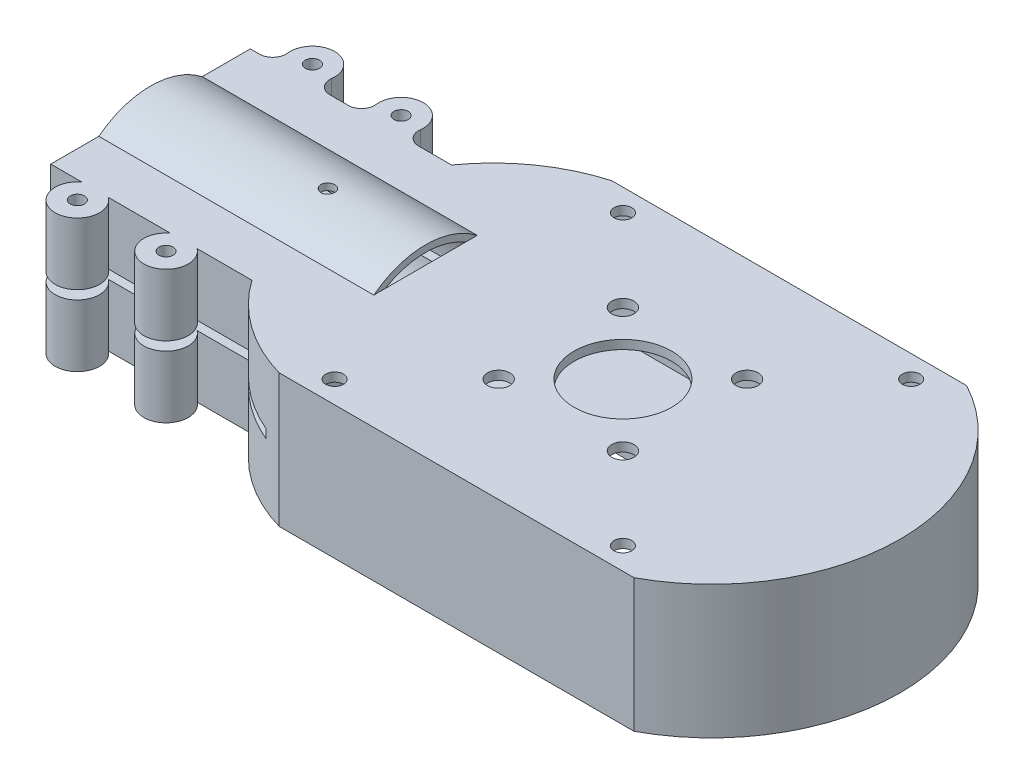
SolidWorks part; units mm, degrees
ref_plane "前视基准面" through (0, 0, 0) normal (0, 0, 1) x (1, 0, 0)
ref_plane "上视基准面" through (0, 0, 0) normal (0, 1, 0) x (1, 0, 0)
ref_plane "右视基准面" through (0, 0, 0) normal (1, 0, 0) x (0, 0, -1)
sketch "草图1" plane through (0, 0, 0) normal (0, 1, 0) x (1, 0, 0)
  line L1 (-40, -37.5) -> (40, -37.5)
  line L2 (-40, -37.5) -> (-40, 37.5)
  line L3 (-40, 37.5) -> (40, 37.5)
  line L4 (40, -37.5) -> (40, 37.5)
  line L5 (-40, -37.5) -> (40, 37.5) construction
  line L6 (-40, 37.5) -> (40, -37.5) construction
  arc A1 (-40, 37.5) -> (-40, -37.5) centre (-29.2879, 0) ccw
  arc A2 (40, -37.5) -> (40, 37.5) centre (20, 0) ccw
  point P0 (0, 0)
  dimension "D3" = 42.5
  dimension "D4" = 78
  dimension "D1" = 75
  dimension "D2" = 80
extrude "凸台-拉伸1" add sketch "草图1" along normal mid plane 30 contours L2 A1 | L1 L4 L3 L2 | L4 A2
ref_plane "基准面1" through (62.5, 0, 0) normal (1, 0, 0) x (0, 0, -1)
ref_plane "基准面2" through (-106.5, 0, 0) normal (1, 0, 0) x (0, 0, -1)
sketch "草图2" plane through (-106.5, 0, 0) normal (1, 0, 0) x (0, 0, -1)
  line L0 (37.5, 15) -> (-37.5, 15) construction
  line L1 (-22.5, -15) -> (22.5, -15)
  line L2 (-22.5, -15) -> (-22.5, 15)
  line L3 (-22.5, 15) -> (22.5, 15)
  line L4 (22.5, -15) -> (22.5, 15)
  line L5 (-22.5, -15) -> (22.5, 15) construction
  line L6 (-22.5, 15) -> (22.5, -15) construction
  point P0 (0, 0)
  dimension "D1" = 45
extrude "凸台-拉伸2" add sketch "草图2" along normal up to surface (45.357 mm away)
sketch "草图3" plane through (-106.5, 0, 0) normal (-1, 0, 0) x (0, 0, 1)
  circle A0 centre (0, 0) radius 19
  dimension "D1" = 38
extrude "凸台-拉伸3" add sketch "草图3" against normal blind 62
sketch "草图4" plane through (-106.5, 0, 0) normal (-1, 0, 0) x (0, 0, 1)
  circle A0 centre (0, 0) radius 17.5
  dimension "D1" = 35
extrude "切除-拉伸1" cut sketch "草图4" against normal blind 62
sketch "草图5" plane through (-106.5, 0, 0) normal (-1, 0, 0) x (0, 0, 1)
  line L1 (-39.0777, -1) -> (39.0777, -1)
  line L2 (-39.0777, -1) -> (-39.0777, 1)
  line L3 (-39.0777, 1) -> (39.0777, 1)
  line L4 (39.0777, -1) -> (39.0777, 1)
  line L5 (-39.0777, -1) -> (39.0777, 1) construction
  line L6 (-39.0777, 1) -> (39.0777, -1) construction
  point P0 (0, 0)
  dimension "D1" = 2
sketch "草图6" plane through (0, 15, 0) normal (0, 1, 0) x (1, 0, 0)
  line L0 (-61.143, 22.5) -> (-106.5, 22.5) construction
  line L1 (-106.5, 22.5) -> (-106.5, 11.6619) construction
  circle A0 centre (-96.5, 26.5) radius 5
  circle A1 centre (-76.5, 26.5) radius 5
  dimension "D1" = 4
  dimension "D2" = 10
  dimension "D3" = 20
  dimension "D4" = 10
  dimension "D5" = 10
extrude "凸台-拉伸4" add sketch "草图6" against normal up to surface (30 mm away) up to face at (-50.4537, -15, 0)
fillet "圆角1" radius 3 4 edges at (-93.5, 0, -22.5) (-99.5, 0, -22.5) (-73.5, 0, -22.5) (-79.5, 0, -22.5)
mirror "镜向3" about plane through (0, 0, 0) normal (0, 0, 1) of "凸台-拉伸4"
sketch "草图7" plane through (0, 15, 0) normal (0, 1, 0) x (1, 0, 0)
  circle A0 centre (-96.5, 26.5) radius 1.6
  circle A1 centre (-76.5, 26.5) radius 1.6
  circle A2 centre (-76.5, -26.5) radius 1.6
  circle A3 centre (-96.5, -26.5) radius 1.6
  dimension "D1" = 3.2
extrude "切除-拉伸3" cut sketch "草图7" against normal blind 62
extrude "切除-拉伸4" cut sketch "草图5" against normal blind 62 contours L1 L4 L3 L2
sketch "草图8" plane through (0, -15, 0) normal (0, -1, 0) x (1, 0, 0)
  circle A0 centre (0, 0) radius 11
  dimension "D1" = 22
extrude "切除-拉伸5" cut sketch "草图8" against normal blind 62
sketch "草图9" plane through (0, -15, 0) normal (0, -1, 0) x (1, 0, 0)
  line L1 (-14, -14) -> (14, -14) construction
  line L2 (-14, -14) -> (-14, 14) construction
  line L3 (-14, 14) -> (14, 14) construction
  line L4 (14, -14) -> (14, 14) construction
  line L5 (-14, -14) -> (14, 14) construction
  line L6 (-14, 14) -> (14, -14) construction
  circle A0 centre (14, 14) radius 2.5
  circle A1 centre (14, -14) radius 2.5
  circle A2 centre (-14, -14) radius 2.5
  circle A3 centre (-14, 14) radius 2.5
  point P0 (0, 0)
  dimension "D3" = 5
  dimension "D1" = 28
  dimension "D2" = 28
extrude "切除-拉伸6" cut sketch "草图9" against normal through all
sketch "草图10" plane through (0, 15, 0) normal (0, 1, 0) x (1, 0, 0)
  line L1 (-32.5, -32.5) -> (32.5, -32.5) construction
  line L2 (-32.5, -32.5) -> (-32.5, 32.5) construction
  line L3 (-32.5, 32.5) -> (32.5, 32.5) construction
  line L4 (32.5, -32.5) -> (32.5, 32.5) construction
  line L5 (-32.5, -32.5) -> (32.5, 32.5) construction
  line L6 (-32.5, 32.5) -> (32.5, -32.5) construction
  circle A0 centre (32.5, 32.5) radius 2
  circle A1 centre (-32.5, 32.5) radius 2
  circle A2 centre (-32.5, -32.5) radius 2
  circle A3 centre (32.5, -32.5) radius 2
  point P0 (0, 0)
  dimension "D3" = 4
  dimension "D1" = 65
  dimension "D2" = 65
extrude "切除-拉伸7" cut sketch "草图10" against normal through all
sketch "草图11" plane through (0, -15, 0) normal (0, -1, 0) x (1, 0, 0)
  line L20 (-44.5, 0) -> (-44.5, 33.7282)
  line L21 (-44.5, -11.6619) -> (-44.5, 11.6619) construction
  line L22 (-40, -35.5) -> (39.4936, -35.5)
  line L23 (39.4936, 35.5) -> (-39.7162, 35.5)
  line L24 (-40, -35.5) -> (39.4936, -35.5)
  line L25 (39.4936, 35.5) -> (-39.7162, 35.5)
  line L26 (-44.5, 0) -> (-44.5, -33.7282)
  arc A18 (39.4936, -35.5) -> (39.4936, 35.5) centre (20, 0) ccw
  arc A19 (-39.7162, 35.5) -> (-59.5094, 21.3462) centre (-29.2879, 0) ccw
  arc A20 (39.4936, -35.5) -> (39.4936, 35.5) centre (20, 0) ccw
  arc A21 (-39.7162, 35.5) -> (-44.5, 33.7282) centre (-29.2879, 0) ccw
  arc A22 (-59.5094, -21.3462) -> (-39.4507, -35.5769) centre (-29.2879, 0) ccw
  arc A23 (-44.5, -33.7282) -> (-39.4507, -35.5769) centre (-29.2879, 0) ccw
  circle M6 centre (32.5, 32.5) radius 2
  circle M7 centre (-32.5, 32.5) radius 2
  circle M8 centre (-32.5, -32.5) radius 2
  circle M9 centre (32.5, -32.5) radius 2
  circle M10 centre (-14, 14) radius 2.5
  circle M11 centre (-14, -14) radius 2.5
  circle M12 centre (14, -14) radius 2.5
  circle M13 centre (14, 14) radius 2.5
  circle M14 centre (0, 0) radius 11
  line M26 (-44.5, 11.6619) -> (-44.5, 9.0139)
  line M27 (-44.5, 9.0139) -> (-44.5, -9.0139)
  line M28 (-44.5, -9.0139) -> (-44.5, -11.6619)
  dimension "D1" = 2
  dimension "D2" = 2
extrude "切除-拉伸8" cut sketch "草图11" against normal blind 28 contours L26 A23 L24 A20 L25 A21 L20 M26 M27 M28 M6 M8 M10 M12 M14 M13 M11 M9 M7
sketch "草图12" plane through (0, -15, 0) normal (0, -1, 0) x (1, 0, 0)
  line L0 (-44.5, 11.6619) -> (-44.5, -11.6619)
  line L2 (-36, -14.75) -> (36, -14.75)
  line L3 (-36, -14.75) -> (-36, 14.75)
  line L4 (-36, 14.75) -> (36, 14.75)
  line L5 (36, -14.75) -> (36, 14.75)
  line L6 (-36, -14.75) -> (36, 14.75) construction
  line L7 (-36, 14.75) -> (36, -14.75) construction
  line L16 (-44.5, -33.7282) -> (-44.5, -11.6619)
  line L17 (-44.5, -11.6619) -> (-106.5, -11.6619)
  line L18 (-106.5, -11.6619) -> (-106.5, -22.5)
  line L19 (-106.5, -22.5) -> (-104.4373, -22.5)
  line L20 (-88.5627, -22.5) -> (-84.4373, -22.5)
  line L21 (-68.5627, -22.5) -> (-61.143, -22.5)
  line L22 (-40, -37.5) -> (40, -37.5)
  line L23 (40, 37.5) -> (-40, 37.5)
  line L24 (-61.143, 22.5) -> (-73.5, 22.5)
  line L25 (-79.5, 22.5) -> (-93.5, 22.5)
  line L26 (-99.5, 22.5) -> (-106.5, 22.5)
  line L27 (-106.5, 22.5) -> (-106.5, 11.6619)
  line L28 (-106.5, 11.6619) -> (-44.5, 11.6619)
  line L29 (-44.5, 11.6619) -> (-44.5, 33.7282)
  line L30 (-39.7162, 35.5) -> (39.4936, 35.5)
  line L31 (39.4936, -35.5) -> (-39.7162, -35.5)
  line L32 (-44.5, -33.7282) -> (-44.5, -11.6619)
  line L38 (-40, -37.5) -> (40, -37.5)
  line L39 (40, 37.5) -> (-40, 37.5)
  line L45 (-44.5, 11.6619) -> (-44.5, 33.7282)
  line L46 (-39.7162, 35.5) -> (39.4936, 35.5)
  line L47 (39.4936, -35.5) -> (-39.7162, -35.5)
  arc A14 (-44.5, -33.7282) -> (-39.7162, -35.5) centre (-29.2879, 0) ccw
  arc A15 (-101.4608, -25.875) -> (-104.4373, -22.5) centre (-104.4373, -25.5) ccw
  arc A16 (-101.4608, -25.875) -> (-91.5392, -25.875) centre (-96.5, -26.5) ccw
  arc A17 (-88.5627, -22.5) -> (-91.5392, -25.875) centre (-88.5627, -25.5) ccw
  arc A18 (-81.4608, -25.875) -> (-84.4373, -22.5) centre (-84.4373, -25.5) ccw
  arc A19 (-81.4608, -25.875) -> (-71.5392, -25.875) centre (-76.5, -26.5) ccw
  arc A20 (-68.5627, -22.5) -> (-71.5392, -25.875) centre (-68.5627, -25.5) ccw
  arc A21 (-61.143, -22.5) -> (-40, -37.5) centre (-29.2879, 0) ccw
  arc A22 (40, -37.5) -> (40, 37.5) centre (20, 0) ccw
  arc A23 (-40, 37.5) -> (-61.143, 22.5) centre (-29.2879, 0) ccw
  arc A24 (-73.5, 22.5) -> (-79.5, 22.5) centre (-76.5, 26.5) ccw
  arc A25 (-93.5, 22.5) -> (-99.5, 22.5) centre (-96.5, 26.5) ccw
  arc A26 (-39.7162, 35.5) -> (-44.5, 33.7282) centre (-29.2879, 0) ccw
  arc A27 (39.4936, -35.5) -> (39.4936, 35.5) centre (20, 0) ccw
  arc A28 (-44.5, -33.7282) -> (-39.7162, -35.5) centre (-29.2879, 0) ccw
  arc A36 (40, -37.5) -> (40, 37.5) centre (20, 0) ccw
  arc A40 (-39.7162, 35.5) -> (-44.5, 33.7282) centre (-29.2879, 0) ccw
  arc A41 (39.4936, -35.5) -> (39.4936, 35.5) centre (20, 0) ccw
  point P0 (0, 0)
  arc M37 (-39.7162, -35.5) -> (-44.5, -33.7282) centre (-29.2879, 0) cw
  line M38 (-44.5, -33.7282) -> (-44.5, -11.6619)
  line M62 (-44.5, 11.6619) -> (-44.5, 33.7282)
  arc M63 (-44.5, 33.7282) -> (-39.7162, 35.5) centre (-29.2879, 0) cw
  line M64 (-39.7162, 35.5) -> (39.4936, 35.5)
  arc M65 (39.4936, 35.5) -> (39.4936, -35.5) centre (20, 0) cw
  line M66 (39.4936, -35.5) -> (-39.7162, -35.5)
  dimension "D2" = 72
  dimension "D3" = 29.5
  dimension "D1" = 0
extrude "凸台-拉伸6" add sketch "草图12" against normal blind 2 contours L0 L5 L2 L3 L4 M62 M38 M37 M66 M65 M64 M63
sketch "草图13" plane through (0, -15, 0) normal (0, -1, 0) x (1, 0, 0)
  line L1 (-44.75, -19) -> (44.75, -19) construction
  line L2 (-44.75, -19) -> (-44.75, 19) construction
  line L3 (-44.75, 19) -> (44.75, 19) construction
  line L4 (44.75, -19) -> (44.75, 19) construction
  line L5 (-44.75, -19) -> (44.75, 19) construction
  line L6 (-44.75, 19) -> (44.75, -19) construction
  circle A0 centre (-44.75, 19) radius 1.5
  circle A1 centre (0, 19) radius 1.5
  circle A2 centre (44.75, 19) radius 1.5
  circle A3 centre (44.75, -19) radius 1.5
  circle A4 centre (0, -19) radius 1.5
  circle A5 centre (-44.75, -19) radius 1.5
  point P0 (0, 0)
  dimension "D3" = 3
  dimension "D1" = 38
  dimension "D2" = 89.5
extrude "切除-拉伸9" cut sketch "草图13" against normal blind 2
sketch "草图14" plane through (0, 0, 0) normal (0, 1, 0) x (1, 0, 0)
  line L0 (-44.5, 9.0139) -> (-44.5, -9.0139) construction
  circle A0 centre (-66.5, 0) radius 1.55
  dimension "D1" = 22
  dimension "D2" = 3.1
extrude "切除-拉伸10" cut sketch "草图14" against normal mid plane 500
